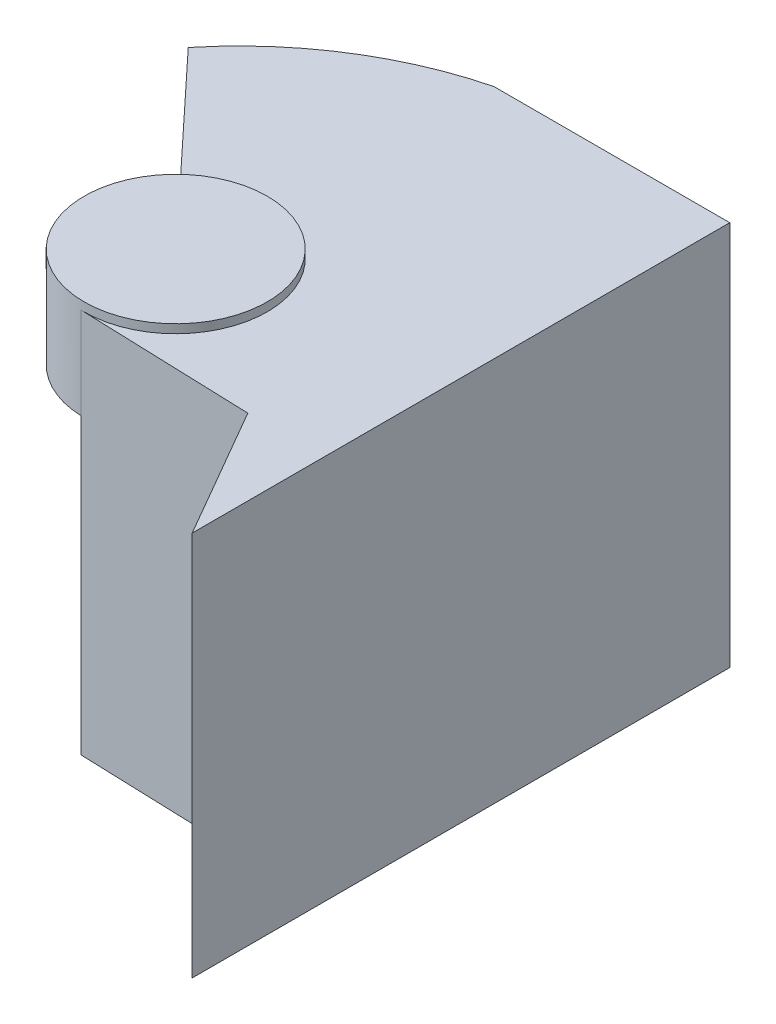
SolidWorks part; units mm, degrees
ref_plane "Front Plane" through (0, 0, 0) normal (0, 0, 1) x (1, 0, 0)
ref_plane "Top Plane" through (0, 0, 0) normal (0, 1, 0) x (1, 0, 0)
ref_plane "Right Plane" through (0, 0, 0) normal (1, 0, 0) x (0, 0, -1)
sketch "Sketch2" plane through (0, 0, 0) normal (0, 1, 0) x (1, 0, 0)
  line L0 (0, 0) -> (0, -311.1214)
  line L1 (0, 0) -> (-136.4567, 0)
  line L2 (0, -311.1214) -> (-44, -234.9111)
  line L3 (-44, -234.9111) -> (-143.9415, -231.4909)
  line L4 (-143.9415, -231.4909) -> (-142.1288, -178.522)
  line L5 (-142.1288, -178.522) -> (-244.5051, -68.8903)
  arc A0 (-244.5051, -68.8903) -> (-136.4567, 0) centre (-86.9244, -196.8643) cw
  dimension "D1" = 150
  dimension "D2" = 53
  dimension "D3" = 135
  dimension "D4" = 100
  dimension "D5" = 30
  dimension "D6" = 88
extrude "Boss-Extrude1" add sketch "Sketch2" against normal blind 223
sketch "Sketch3" plane through (0, 0, 0) normal (0, 1, 0) x (1, 0, 0)
  circle A0 centre (-142.1288, -178.522) radius 53
extrude "Boss-Extrude2" add sketch "Sketch3" along normal blind 5 and the other way blind 53
